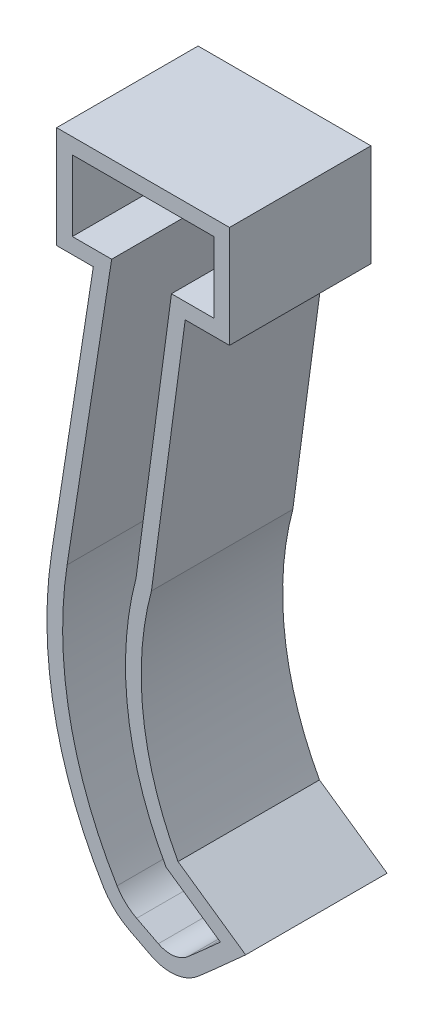
SolidWorks part; units mm, degrees
ref_plane "前视基准面" through (0, 0, 0) normal (0, 0, 1) x (1, 0, 0)
ref_plane "上视基准面" through (0, 0, 0) normal (0, 1, 0) x (1, 0, 0)
ref_plane "右视基准面" through (0, 0, 0) normal (1, 0, 0) x (0, 0, -1)
sketch "草图2" plane through (0, 0, 0) normal (0, 0, 1) x (1, 0, 0)
  line L0 (-30.0658, -26.3827) -> (-32.054, -28.1273)
  line L1 (-47.4321, 7.362) -> (-41.7629, 43.8874)
  line L3 (-34.1521, 43.8874) -> (-38.6651, 10.2473)
  line L4 (-38.5803, -27.1659) -> (-35.8195, -28.5894)
  line L6 (-46.7629, 52.8874) -> (-28.7629, 52.8874)
  line L7 (-41.7629, 43.8874) -> (-46.7629, 43.8874)
  line L8 (-30.0658, -26.3827) -> (-27.9262, -24.4632)
  line L9 (-27.9262, -24.4632) -> (-34.8339, -19.6622)
  line L10 (-28.7629, 52.8874) -> (-28.7629, 43.8874)
  line L11 (-28.7629, 43.8874) -> (-34.1521, 43.8874)
  line L12 (-46.7629, 43.8874) -> (-46.7629, 52.8874)
  line L14 (-48.7629, 54.8874) -> (-26.7629, 54.8874)
  line L15 (-26.7629, 54.8874) -> (-26.7629, 41.8874)
  line L16 (-26.7629, 41.8874) -> (-32.4024, 41.8874)
  line L17 (-32.4024, 41.8874) -> (-36.6999, 9.855)
  line L18 (-24.7088, -24.2638) -> (-33.3119, -18.2844)
  line L19 (-28.7384, -27.8788) -> (-24.7088, -24.2638)
  line L20 (-28.7384, -27.8788) -> (-30.7349, -29.6306)
  line L21 (-39.4968, -28.9435) -> (-36.7361, -30.367)
  line L22 (-49.4084, 7.6687) -> (-44.0973, 41.8874)
  line L23 (-44.0973, 41.8874) -> (-48.7629, 41.8874)
  line L24 (-48.7629, 41.8874) -> (-48.7629, 54.8874)
  arc A1 (-38.6651, 10.2473) -> (-34.8339, -19.6622) centre (0, 0) ccw
  arc A2 (-47.4321, 7.362) -> (-41.0775, -24.8323) centre (0, 0) ccw
  arc A4 (-41.0775, -24.8323) -> (-38.5803, -27.1659) centre (-35.7013, -21.5822) ccw
  arc A5 (-35.8195, -28.5894) -> (-32.054, -28.1273) centre (-34.2758, -25.5954) ccw
  arc A9 (-36.6999, 9.855) -> (-33.3119, -18.2844) centre (0, 0) ccw
  arc A10 (-36.7361, -30.367) -> (-30.7349, -29.6306) centre (-34.2758, -25.5954) ccw
  arc A11 (-42.789, -25.8669) -> (-39.4968, -28.9435) centre (-35.7013, -21.5822) ccw
  arc A12 (-49.4084, 7.6687) -> (-42.789, -25.8669) centre (0, 0) ccw
  dimension "D1" = 2
  dimension "D2" = 80
  dimension "D3" = 96
  dimension "D4" = 18
  dimension "D5" = 9
  dimension "D6" = 5
extrude "凸台-拉伸1" add sketch "草图2" along normal blind 16
sketch "草图3" plane through (0, 0, 0) normal (0, 0, -1) x (-1, 0, 0)
  line L0 (24.7088, -24.2638) -> (33.3119, -18.2844) construction
  line L1 (30.7349, -29.6306) -> (28.7384, -27.8788) construction
  line L2 (28.7384, -27.8788) -> (24.7088, -24.2638) construction
  line L3 (39.4968, -28.9435) -> (36.7361, -30.367) construction
  line L4 (44.0973, 41.8874) -> (49.4084, 7.6687) construction
  line L5 (48.7629, 41.8874) -> (44.0973, 41.8874) construction
  line L6 (48.7629, 54.8874) -> (48.7629, 41.8874) construction
  line L7 (26.7629, 54.8874) -> (48.7629, 54.8874) construction
  line L8 (36.6999, 9.855) -> (32.4024, 41.8874) construction
  line L9 (32.4024, 41.8874) -> (26.7629, 41.8874) construction
  line L10 (26.7629, 41.8874) -> (26.7629, 54.8874) construction
  line L11 (24.7088, -24.2638) -> (33.3119, -18.2844)
  line L12 (30.7349, -29.6306) -> (28.7384, -27.8788)
  line L13 (28.7384, -27.8788) -> (24.7088, -24.2638)
  line L14 (39.4968, -28.9435) -> (36.7361, -30.367)
  line L15 (44.0973, 41.8874) -> (49.4084, 7.6687)
  line L16 (48.7629, 41.8874) -> (44.0973, 41.8874)
  line L17 (48.7629, 54.8874) -> (48.7629, 41.8874)
  line L18 (26.7629, 54.8874) -> (48.7629, 54.8874)
  line L19 (36.6999, 9.855) -> (32.4024, 41.8874)
  line L20 (32.4024, 41.8874) -> (26.7629, 41.8874)
  line L21 (26.7629, 41.8874) -> (26.7629, 54.8874)
  arc A0 (33.3119, -18.2844) -> (36.6999, 9.855) centre (0, 0) ccw construction
  arc A1 (30.7349, -29.6306) -> (36.7361, -30.367) centre (34.2758, -25.5954) ccw construction
  arc A2 (39.4968, -28.9435) -> (42.789, -25.8669) centre (35.7013, -21.5822) ccw construction
  arc A3 (42.789, -25.8669) -> (49.4084, 7.6687) centre (0, 0) ccw construction
  arc A4 (33.3119, -18.2844) -> (36.6999, 9.855) centre (0, 0) ccw
  arc A5 (30.7349, -29.6306) -> (36.7361, -30.367) centre (34.2758, -25.5954) ccw
  arc A6 (39.4968, -28.9435) -> (42.789, -25.8669) centre (35.7013, -21.5822) ccw
  arc A7 (42.789, -25.8669) -> (49.4084, 7.6687) centre (0, 0) ccw
extrude "凸台-拉伸2" add sketch "草图3" along normal blind 2
